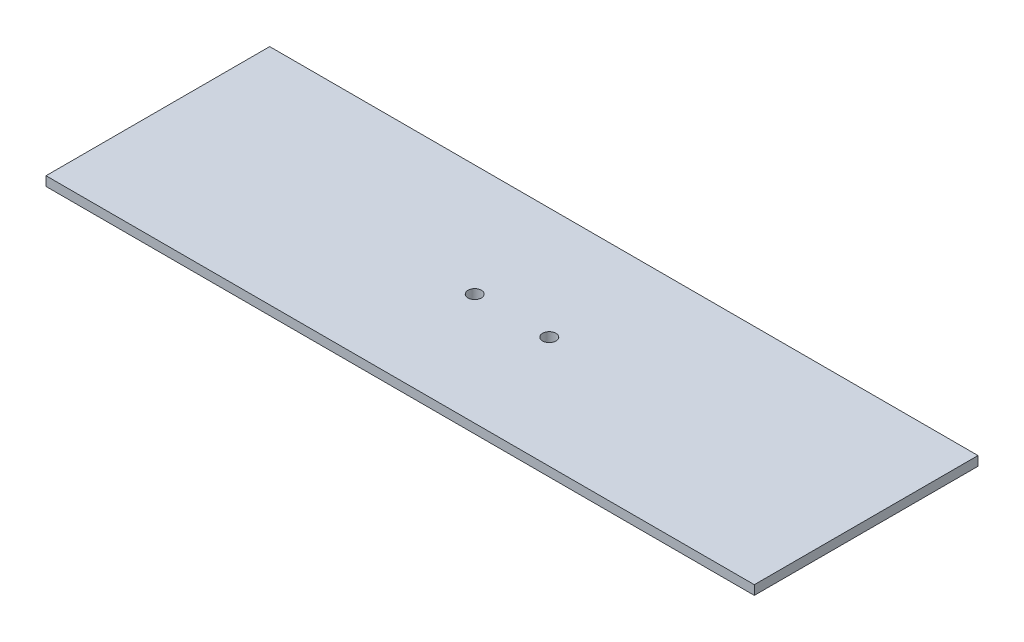
SolidWorks part; units mm, degrees
ref_plane "Front Plane" through (0, 0, 0) normal (0, 0, 1) x (1, 0, 0)
ref_plane "Top Plane" through (0, 0, 0) normal (0, 1, 0) x (1, 0, 0)
ref_plane "Right Plane" through (0, 0, 0) normal (1, 0, 0) x (0, 0, -1)
sketch "Sketch1" plane through (0, 0, 0) normal (0, 1, 0) x (1, 0, 0)
  line L0 (-12.7, 0) -> (12.7, 0) construction
  line L1 (120.65, -38.1) -> (-120.65, -38.1)
  line L2 (120.65, -38.1) -> (120.65, 38.1)
  line L3 (120.65, 38.1) -> (-120.65, 38.1)
  line L4 (-120.65, -38.1) -> (-120.65, 38.1)
  line L5 (120.65, -38.1) -> (-120.65, 38.1) construction
  line L6 (120.65, 38.1) -> (-120.65, -38.1) construction
  circle A0 centre (-12.7, 0) radius 2.286
  circle A1 centre (12.7, 0) radius 2.286
  point P0 (0, 0)
  point P9 (0, 0)
  dimension "D4" = 4.572
  dimension "D1" = 241.3
  dimension "D2" = 76.2
  dimension "D3" = 25.4
extrude "Boss-Extrude1" add sketch "Sketch1" along normal blind 3.175
